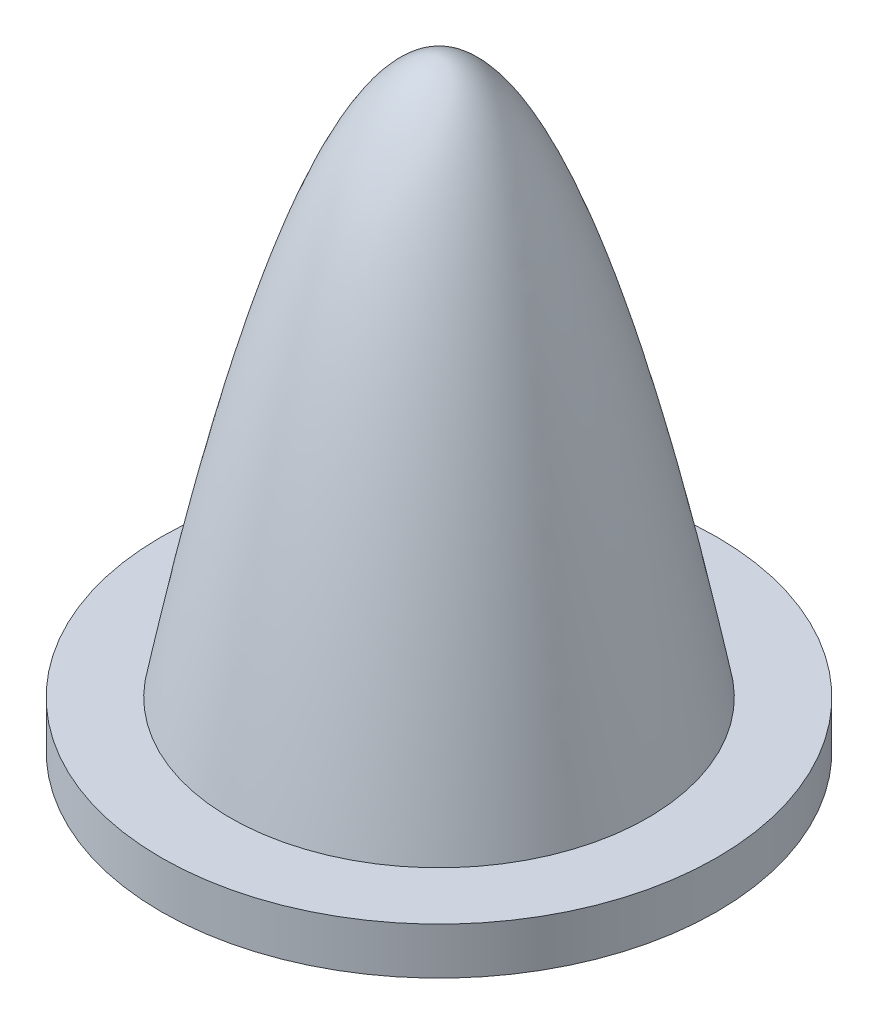
SolidWorks part; units mm, degrees
ref_plane "Front Plane" through (0, 0, 0) normal (0, 0, 1) x (1, 0, 0)
ref_plane "Top Plane" through (0, 0, 0) normal (0, 1, 0) x (1, 0, 0)
ref_plane "Right Plane" through (0, 0, 0) normal (1, 0, 0) x (0, 0, -1)
sketch "Sketch1" plane through (0, 0, 0) normal (0, 0, 1) x (1, 0, 0)
  line L0 (0, 0) -> (0, 12.87)
  line L1 (0, 0) -> (-5.94, 0)
  line L2 (-5.94, 0) -> (-5.94, 1)
  line L3 (-5.94, 1) -> (-4.465, 1)
  line L4 (0, 12.87) -> (-2.2442, 12.7838) construction
  line L5 (-2.2442, 12.7838) -> (-4.465, 1) construction
  spline S0 degree 2 poles (0, 12.87) (-2.2442, 12.7838) (-4.465, 1) knots 0 0 0 1 1 1
  dimension "D1" = 12.87
  dimension "D2" = 1
  dimension "D3" = 5.94
  dimension "D4" = 1.475
  dimension "D5" = 2.2442
  dimension "D6" = 12.7838
revolve "Revolve1" add sketch "Sketch1" angle 360 about L0
hole_wizard "#10-24 Tapped Hole1" positions "Sketch6" profile "Sketch5" tap size "#10-24" standard "ANSI Inch"
sketch "Sketch6" plane through (0, 0, 0) normal (0, -1, 0) x (-1, 0, 0)
  point P0 (0, 0)
sketch "Sketch5" plane through (0, 0, 0) normal (1, 0, 0) x (0, 0, -1)
  line L0 (0, 0) -> (0, 9.6408)
  line L1 (0, 9.6408) -> (1.8986, 8.5)
  line L2 (1.8986, 8.5) -> (1.8986, 0)
  line L5 (1.8986, 0) -> (0, 0)
  line L10 (0, 9.6408) -> (-1.8987, 8.5) construction
  line L11 (0, -6.35) -> (0, 107.95) construction
  dimension "Tap Drill Dia." = 3.7973
  dimension "Tap Drill Depth" = 8.5
  dimension "Drill Angle" = 118
cosmetic thread "Hole Thread1" parameters "D1"=8, "D2"=4.826
